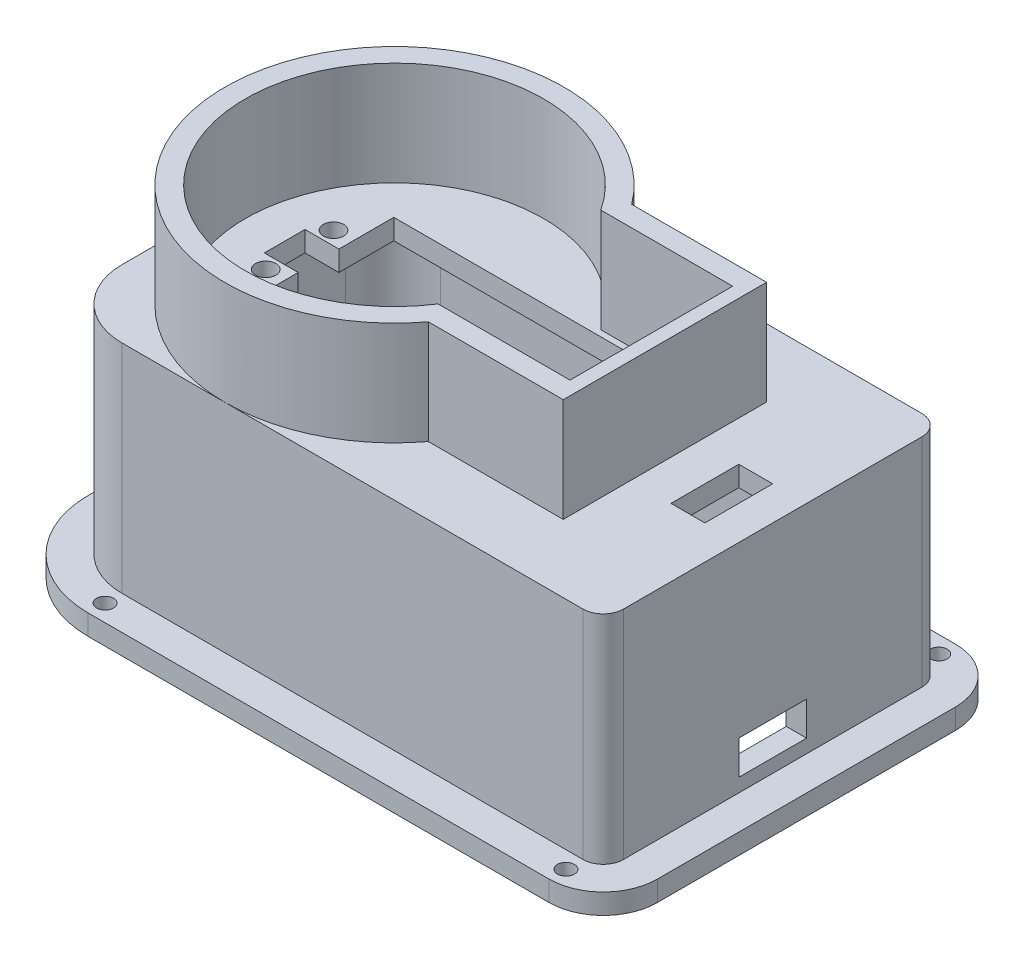
SolidWorks part; units mm, degrees
ref_plane "Front Plane" through (0, 0, 0) normal (0, 0, 1) x (1, 0, 0)
ref_plane "Top Plane" through (0, 0, 0) normal (0, 1, 0) x (1, 0, 0)
ref_plane "Right Plane" through (0, 0, 0) normal (1, 0, 0) x (0, 0, -1)
sketch "Sketch1" plane through (0, 0, 0) normal (0, 1, 0) x (1, 0, 0)
  line L0 (-21.1, 3) -> (-26.1, 3)
  line L1 (-26.1, 3) -> (-26.1, -3)
  line L2 (-26.1, -3) -> (-21.1, -3)
  line L3 (-21.1, -3) -> (-21.1, -11.1)
  line L4 (-21.1, -11.1) -> (21.1, -11.1)
  line L5 (21.1, 11.1) -> (21.1, -11.1)
  line L6 (-21.1, 11.1) -> (21.1, 11.1)
  line L7 (-21.1, 11.1) -> (-21.1, 3)
  line L9 (-35.1, 25) -> (45.9, 25)
  line L10 (-35.1, 25) -> (-35.1, -25)
  line L11 (-35.1, -25) -> (45.9, -25)
  line L12 (45.9, 25) -> (45.9, -25)
  circle A0 centre (-23.9, 5) radius 1.5
  circle A1 centre (-23.9, -5) radius 1.5
  circle A2 centre (24.1, 5) radius 1.5
  circle A3 centre (24.1, -5) radius 1.5
  point P0 (0, 0)
  point P2 (-26.1, 0)
  point P20 (5.9, 0)
  dimension "D3" = 3
  dimension "D4" = 3
  dimension "D5" = 3
  dimension "D11" = 3
  dimension "D1" = 6
  dimension "D2" = 5
  dimension "D6" = 23.9
  dimension "D7" = 5
  dimension "D8" = 23.9
  dimension "D9" = 5
  dimension "D10" = 5
  dimension "D12" = 22.2
  dimension "D13" = 42.2
  dimension "D14" = 11.1
  dimension "D15" = 11.1
  dimension "D16" = 21.1
  dimension "D17" = 8.1
  dimension "D18" = 8.1
  dimension "D19" = 42.2
  dimension "D20" = 26.1
  dimension "D21" = 48
  dimension "D22" = 48
  dimension "D23" = 9
  dimension "D24" = 40
  dimension "D25" = 25
  dimension "D26" = 25
extrude "Boss-Extrude1" add sketch "Sketch1" against normal blind 35
fillet "Fillet1" radius 10 2 edges at (-35.1, -17.5, 25) (-35.1, -17.5, -25)
fillet "Fillet2" radius 3 2 edges at (45.9, -17.5, 25) (45.9, -17.5, -25)
sketch "Sketch2" plane through (0, 0, 0) normal (0, 1, 0) x (1, 0, 0)
  line L0 (-21.1, 11.1) -> (-21.1, 3) construction
  line L1 (10.1, 15) -> (30, 15)
  line L2 (30, 15) -> (30, -15)
  line L3 (30, -15) -> (10.1, -15)
  line L4 (27, -12) -> (10.1, -12) construction
  line L5 (8.5391, 12) -> (27, 12)
  line L6 (27, 12) -> (27, -12)
  line L7 (27, -12) -> (8.5391, -12)
  line L8 (10.1, 12) -> (27, 12) construction
  arc A0 (10.1, 15) -> (10.1, -15) centre (-9.9, 0) ccw
  arc A1 (8.5391, 12) -> (8.5391, -12) centre (-9.9, 0) ccw
  circle A2 centre (-9.9, 0) radius 25 construction
  circle A3 centre (-9.9, 0) radius 22 construction
  dimension "D2" = 50
  dimension "D1" = 11.2
  dimension "D4" = 15
  dimension "D5" = 15
  dimension "D6" = 30
  dimension "D3" = 3
  dimension "D7" = 3
sketch "Sketch3" plane through (0, -35, 0) normal (0, -1, 0) x (1, 0, 0)
  line L0 (42.9, 22) -> (-25.1, 22)
  line L1 (-32.1, 15) -> (-32.1, -15)
  line L2 (-25.1, -22) -> (42.9, -22)
  line L3 (42.9, -22) -> (42.9, 22)
  arc A0 (-25.1, 22) -> (-32.1, 15) centre (-25.1, 15) ccw
  arc A1 (-32.1, -15) -> (-25.1, -22) centre (-25.1, -15) ccw
extrude "Cut-Extrude1" cut sketch "Sketch3" against normal blind 32
extrude "Boss-Extrude2" add sketch "Sketch2" along normal blind 15.3
sketch "Sketch4" plane through (0, 15.3, 0) normal (0, 1, 0) x (1, 0, 0)
  line L1 (27, 12) -> (28, 12)
  line L2 (27, 12) -> (27, -12)
  line L3 (27, -12) -> (28, -12)
  line L4 (28, 12) -> (28, -12)
  dimension "D1" = 1
extrude "Cut-Extrude2" cut sketch "Sketch4" against normal up to surface (15.3 mm away) up to face at (-11.8, 0, 0)
sketch "Sketch5" plane through (45.9, 0, 0) normal (1, 0, 0) x (0, 0, -1)
  line L0 (-22, -35) -> (22, -35) construction
  line L1 (5, -30) -> (-5, -30)
  line L2 (5, -30) -> (5, -25)
  line L3 (5, -25) -> (-5, -25)
  line L4 (-5, -30) -> (-5, -25)
  line L5 (5, -30) -> (-5, -25) construction
  line L6 (5, -25) -> (-5, -30) construction
  point P0 (0, -27.5)
  dimension "D1" = 10
  dimension "D2" = 5
  dimension "D3" = 5
extrude "Cut-Extrude3" cut sketch "Sketch5" against normal blind 16.3
sketch "Sketch6" plane through (0, -35, 0) normal (0, -1, 0) x (1, 0, 0)
  line L0 (42.9, 30) -> (-25.1, 30)
  line L1 (-40.1, 15) -> (-40.1, -15)
  line L2 (-25.1, -30) -> (42.9, -30)
  line L3 (50.9, -22) -> (50.9, 22)
  line L4 (45.9, -22) -> (45.9, 22)
  line L5 (42.9, 25) -> (-25.1, 25)
  line L6 (-35.1, 15) -> (-35.1, -15)
  line L7 (-25.1, -25) -> (42.9, -25)
  line L8 (45.9, -22) -> (45.9, 22)
  line L9 (42.9, 25) -> (-25.1, 25)
  line L10 (-35.1, 15) -> (-35.1, -15)
  line L11 (-25.1, -25) -> (42.9, -25)
  arc A0 (-25.1, 30) -> (-40.1, 15) centre (-25.1, 15) ccw
  arc A1 (-40.1, -15) -> (-25.1, -30) centre (-25.1, -15) ccw
  arc A2 (42.9, -30) -> (50.9, -22) centre (42.9, -22) ccw
  arc A3 (50.9, 22) -> (42.9, 30) centre (42.9, 22) ccw
  arc A4 (45.9, 22) -> (42.9, 25) centre (42.9, 22) ccw
  arc A5 (-25.1, 25) -> (-35.1, 15) centre (-25.1, 15) ccw
  arc A6 (-35.1, -15) -> (-25.1, -25) centre (-25.1, -15) ccw
  arc A7 (42.9, -25) -> (45.9, -22) centre (42.9, -22) ccw
  arc A8 (45.9, 22) -> (42.9, 25) centre (42.9, 22) ccw
  arc A9 (-25.1, 25) -> (-35.1, 15) centre (-25.1, 15) ccw
  arc A10 (-35.1, -15) -> (-25.1, -25) centre (-25.1, -15) ccw
  arc A11 (42.9, -25) -> (45.9, -22) centre (42.9, -22) ccw
  circle A12 centre (-25.1, 27.5) radius 1.25
  circle A13 centre (42.9, 27.5) radius 1.25
  circle A14 centre (42.9, -27.5) radius 1.25
  circle A15 centre (-25.1, -27.5) radius 1.25
  dimension "D3" = 2.5
  dimension "D5" = 2.5
  dimension "D8" = 2.5
  dimension "D10" = 2.5
  dimension "D4" = 2.5
  dimension "D6" = 2.5
  dimension "D7" = 2.5
  dimension "D9" = 2.5
  dimension "D1" = 0
  dimension "D2" = 5
extrude "Boss-Extrude3" add sketch "Sketch6" against normal blind 3
sketch "Sketch7" plane through (0, 0, 0) normal (0, 1, 0) x (1, 0, 0)
  line L0 (45.9, -22) -> (45.9, 22) construction
  line L1 (35.9, 5) -> (40.9, 5)
  line L2 (35.9, 5) -> (35.9, -5)
  line L3 (35.9, -5) -> (40.9, -5)
  line L4 (40.9, 5) -> (40.9, -5)
  line L5 (35.9, 5) -> (40.9, -5) construction
  line L6 (35.9, -5) -> (40.9, 5) construction
  point P0 (38.4, 0)
  dimension "D1" = 10
  dimension "D2" = 5
  dimension "D3" = 5
extrude "Cut-Extrude4" cut sketch "Sketch7" against normal blind 10
